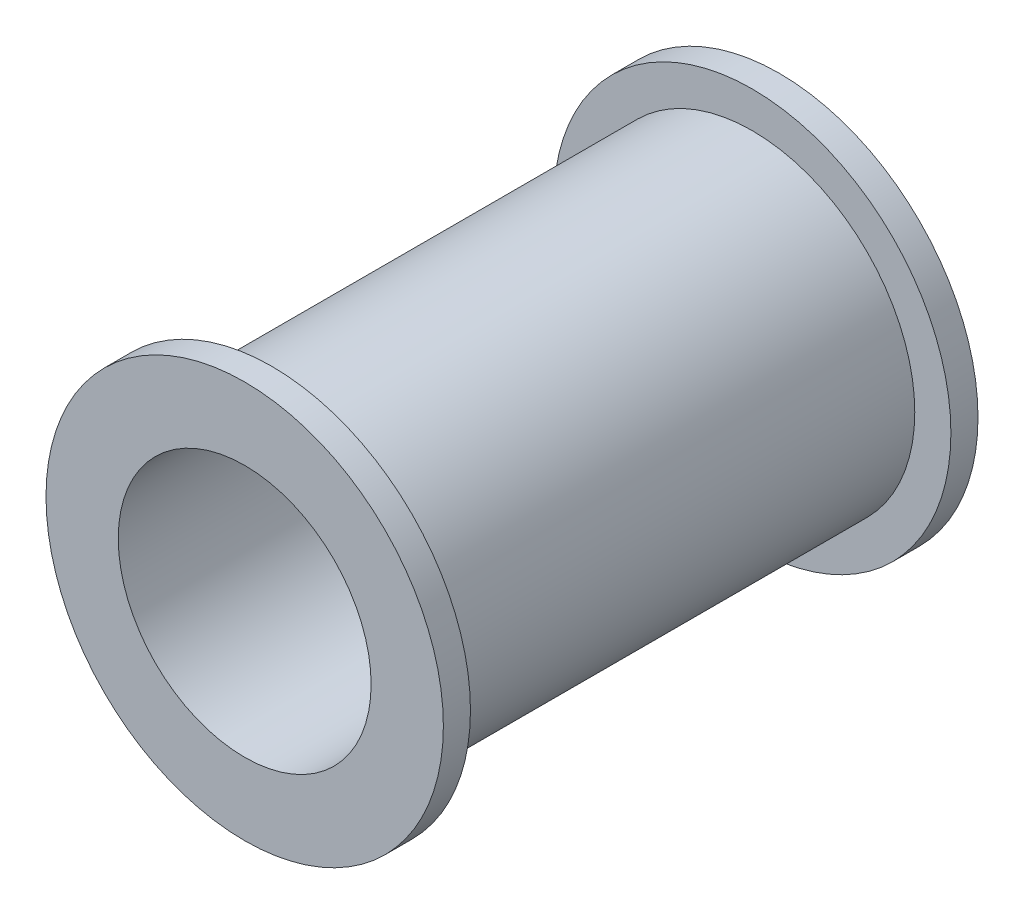
SolidWorks part; units mm, degrees
ref_plane "Alzado" through (0, 0, 0) normal (0, 0, 1) x (1, 0, 0)
ref_plane "Planta" through (0, 0, 0) normal (0, 1, 0) x (1, 0, 0)
ref_plane "Vista lateral" through (0, 0, 0) normal (1, 0, 0) x (0, 0, -1)
sketch "Croquis1" plane through (0, 0, 0) normal (0, 0, 1) x (1, 0, 0)
  circle A0 centre (-4.9763, -25.8) radius 9
  circle A2 centre (-4.9763, -25.8) radius 1.625
  dimension "D1" = 18
  dimension "D2" = 3.25
extrude "Saliente-Extruir1" add sketch "Croquis1" against normal blind 8.9
sketch "Croquis2" plane through (0, 0, 0) normal (0, 0, 1) x (1, 0, 0)
  circle A0 centre (-4.9763, -25.8) radius 9
  circle A1 centre (-4.9763, -25.8) radius 7
  circle A2 centre (-4.9763, -25.8) radius 1.625 construction
  dimension "D1" = 14
  dimension "D2" = 18
extrude "Saliente-Extruir2" add sketch "Croquis2" along normal up to vertex (20.7 mm away)
sketch "Croquis3" plane through (0, 0, -8.9) normal (0, 0, -1) x (-1, 0, 0)
  line L0 (4.9763, -27.3) -> (4.9763, -29.3) construction
  line L1 (8.1463, -29.3) -> (8.1463, -32.3)
  line L2 (4.9763, -29.3) -> (8.1463, -29.3)
  line L3 (4.9763, -29.3) -> (1.8063, -29.3)
  line L4 (8.1463, -32.3) -> (1.8063, -32.3)
  line L5 (1.8063, -32.3) -> (1.8063, -29.3)
  circle A0 centre (4.9763, -25.8) radius 1.625 construction
  dimension "D1" = 3.17
  dimension "D2" = 3.5
  dimension "D3" = 6.5
extrude "Cortar-Extruir1" cut sketch "Croquis3" against normal blind 6.25
sketch "Croquis4" plane through (0, -29.3, 0) normal (0, -1, 0) x (1, 0, 0)
  line L0 (-1.8063, -2.65) -> (-8.1463, -8.9) construction
  circle A0 centre (-4.9763, -5.775) radius 1.625
  dimension "D1" = 3.25
extrude "Cortar-Extruir2" cut sketch "Croquis4" against normal blind 4.25 and the other way blind 7.25
sketch "Croquis7" plane through (0, 0, 20.7) normal (0, 0, 1) x (1, 0, 0)
  circle A0 centre (-4.9763, -25.8) radius 11
  circle A1 centre (-4.9763, -25.8) radius 7
  circle A2 centre (-4.9763, -25.8) radius 9 construction
  dimension "D1" = 14
  dimension "D2" = 22
extrude "Saliente-Extruir3" add sketch "Croquis7" against normal blind 1.5
sketch "Croquis8" plane through (0, 0, -8.9) normal (0, 0, -1) x (-1, 0, 0)
  circle A0 centre (4.9763, -25.8) radius 11
  circle A1 centre (4.9763, -25.8) radius 9
  dimension "D1" = 18
  dimension "D2" = 22
extrude "Saliente-Extruir4" add sketch "Croquis8" against normal blind 1.5
